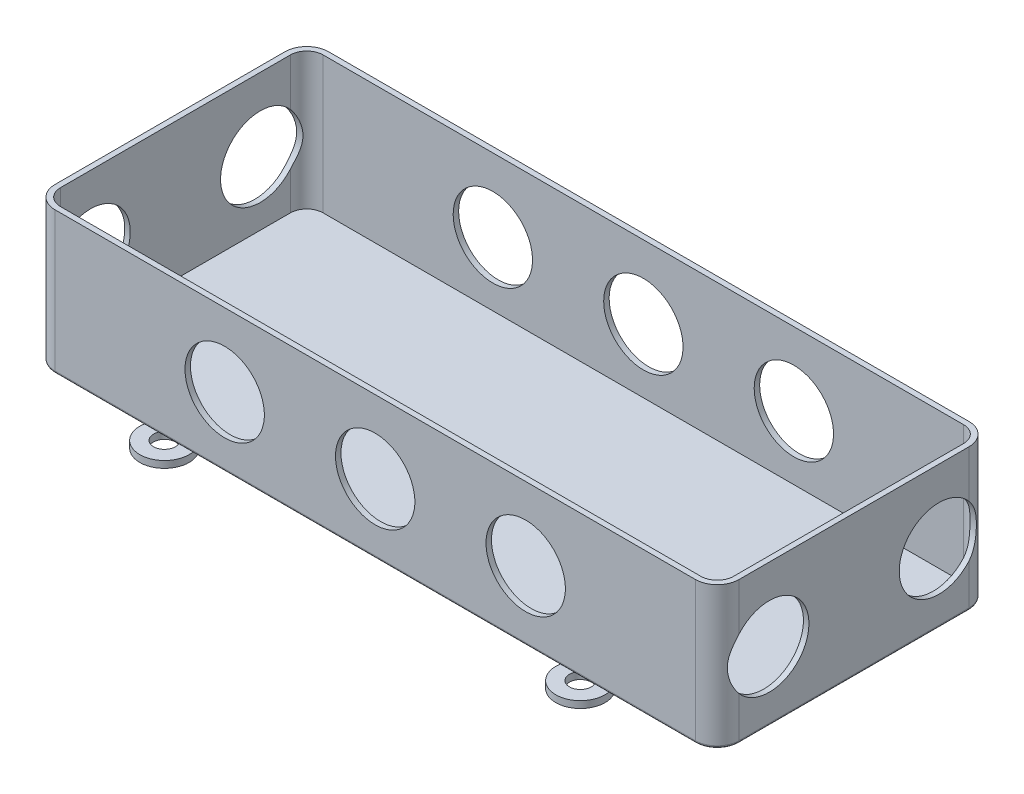
SolidWorks part; units mm, degrees
material "PBT General Purpose"
ref_plane "Front Plane" through (0, 0, 0) normal (0, 0, 1) x (1, 0, 0)
ref_plane "Top Plane" through (0, 0, 0) normal (0, 1, 0) x (1, 0, 0)
ref_plane "Right Plane" through (0, 0, 0) normal (1, 0, 0) x (0, 0, -1)
sketch "Sketch1" plane through (0, 0, 0) normal (0, 1, 0) x (1, 0, 0)
  line L0 (0, 50) -> (0, 0) construction
  line L1 (0, 0) -> (125, 0) construction
  line L2 (125, -42) -> (125, 42)
  line L3 (117, 50) -> (-117, 50)
  line L4 (-125, -42) -> (-125, 42)
  line L5 (117, -50) -> (-117, -50)
  arc A0 (125, 42) -> (117, 50) centre (117, 42) ccw
  arc A1 (-125, 42) -> (-117, 50) centre (-117, 42) cw
  arc A2 (-125, -42) -> (-117, -50) centre (-117, -42) ccw
  arc A3 (125, -42) -> (117, -50) centre (117, -42) cw
  point P17 (-125, 0)
  dimension "D1" = 8
  dimension "D2" = 100
  dimension "D3" = 250
extrude "Boss-Extrude1" add sketch "Sketch1" along normal blind 52
fillet "Fillet1" radius 1 8 edges at (-122.6569, 0, 47.6569) (-125, 0, 0) (-122.6569, 0, -47.6569) (0, 0, -50) (122.6569, 0, -47.6569) (125, 0, 0) (122.6569, 0, 47.6569) (0, 0, 50)
shell "Shell1" thickness 2
sketch "Sketch2" plane through (0, 0, 0) normal (0, -1, 0) x (1, 0, 0)
  line L0 (0, 64.6316) -> (0, 0) construction
  line L1 (0, 0) -> (65.5067, 0) construction
  circle A0 centre (76, 51) radius 4
  circle A1 centre (76, 51) radius 9
  circle A2 centre (76, -51) radius 9
  circle A3 centre (76, -51) radius 4
  circle A4 centre (-76, -51) radius 4
  circle A5 centre (-76, -51) radius 9
  circle A6 centre (-76, 51) radius 9
  circle A7 centre (-76, 51) radius 4
  dimension "D1" = 8
  dimension "D2" = 18
  dimension "D3" = 152
  dimension "D4" = 102
extrude "Boss-Extrude2" add sketch "Sketch2" along normal blind 2.5
sketch "Sketch3" plane through (0, 0, -50) normal (0, 0, -1) x (-1, 0, 0)
  line L0 (0, 0) -> (0, 69.3908) construction
  line L1 (-117, 52) -> (117, 52) construction
  circle A0 centre (-55, 25.3) radius 14.5
  circle A1 centre (0, 25.3) radius 14.5
  circle A2 centre (55, 25.3) radius 14.5
  dimension "D1" = 29
  dimension "D3" = 81
  dimension "D2" = 12.2
extrude "Cut-Extrude1" cut sketch "Sketch3" against normal through all
sketch "Sketch4" plane through (0, 0, 0) normal (1, 0, 0) x (0, 0, -1)
  line L0 (0, 0) -> (0, 62.8314) construction
  line L1 (-42, 52) -> (42, 52) construction
  circle A0 centre (31, 25.3) radius 14.5
  circle A1 centre (-31, 25.3) radius 14.5
  dimension "D1" = 29
  dimension "D2" = 33
  dimension "D3" = 12.2
extrude "Cut-Extrude2" cut sketch "Sketch4" against normal through all and the other way through all
